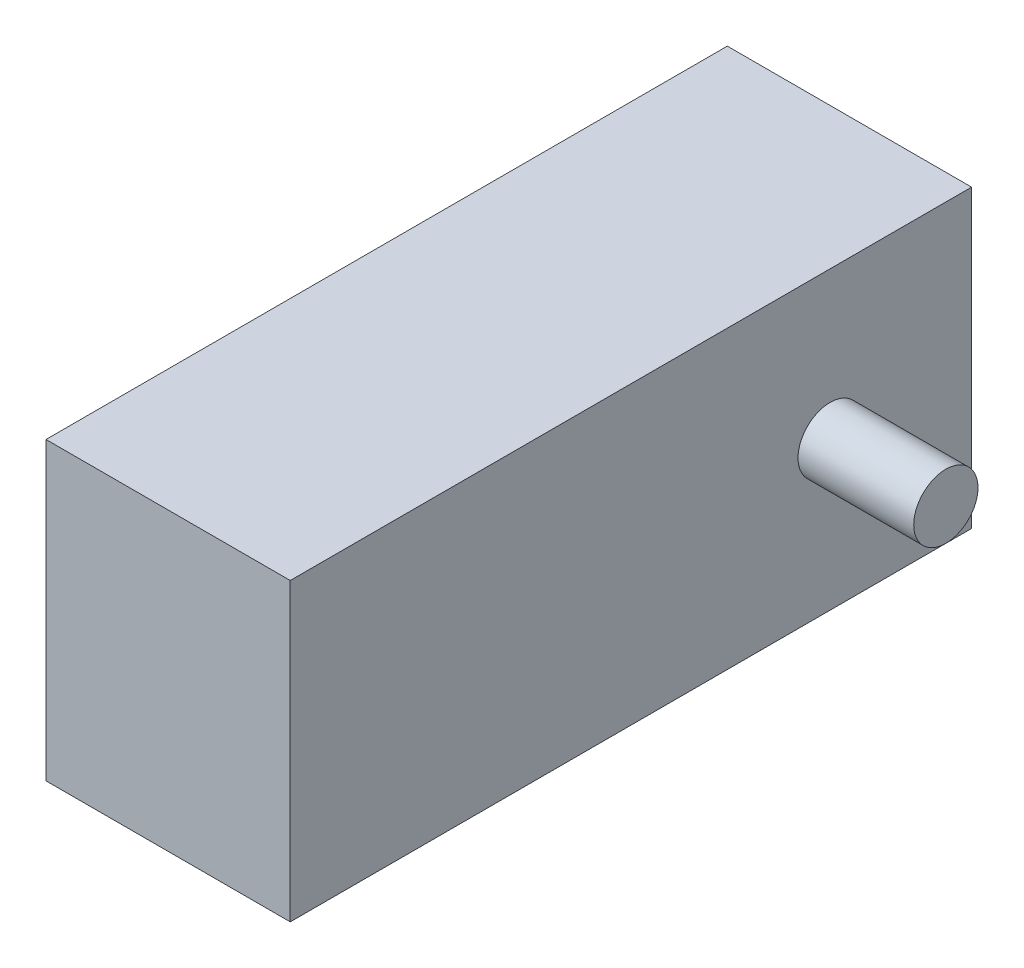
SolidWorks part; units mm, degrees
ref_plane "前视基准面" through (0, 0, 0) normal (0, 0, 1) x (1, 0, 0)
ref_plane "上视基准面" through (0, 0, 0) normal (0, 1, 0) x (1, 0, 0)
ref_plane "右视基准面" through (0, 0, 0) normal (1, 0, 0) x (0, 0, -1)
sketch "草图2" plane through (0, 0, 0) normal (1, 0, 0) x (0, 0, -1)
  line L0 (-35.7487, 38.8704) -> (17.2513, 38.8704)
  line L1 (17.2513, 38.8704) -> (17.2513, 15.8704)
  line L2 (17.2513, 15.8704) -> (-35.7487, 15.8704)
  line L3 (-35.7487, 15.8704) -> (-35.7487, 38.8704)
extrude "凸台-拉伸1" add sketch "草图2" along normal blind 19
sketch "草图3" plane through (19, 0, 0) normal (1, 0, 0) x (0, 0, -1)
  line L0 (17.2513, 15.8704) -> (17.2513, 38.8704) construction
  line L2 (-35.7487, 15.8704) -> (17.2513, 15.8704) construction
  circle A0 centre (6.2513, 27.3704) radius 2.5
  point P4 (17.2513, 27.3704)
  dimension "D1" = 11
  dimension "D2" = 11.5
extrude "凸台-拉伸2" add sketch "草图3" along normal blind 9
sketch "草图7" plane through (0, 0, 0) normal (-1, 0, 0) x (0, 0, 1)
  line L1 (-17.2513, 15.8704) -> (-17.2513, 38.8704) construction
  line L4 (-17.2513, 38.8704) -> (35.7487, 38.8704) construction
  circle A0 centre (-6.2513, 27.3704) radius 2.5
  point P6 (-6.4378, 16.2443)
  point P9 (-6.661, 15.8704)
  point P10 (0, 0)
  dimension "D1" = 11
  dimension "D2" = 11.5
extrude "凸台-拉伸5" add sketch "草图7" along normal blind 9
equation "\"11。5\"=11.1212"
